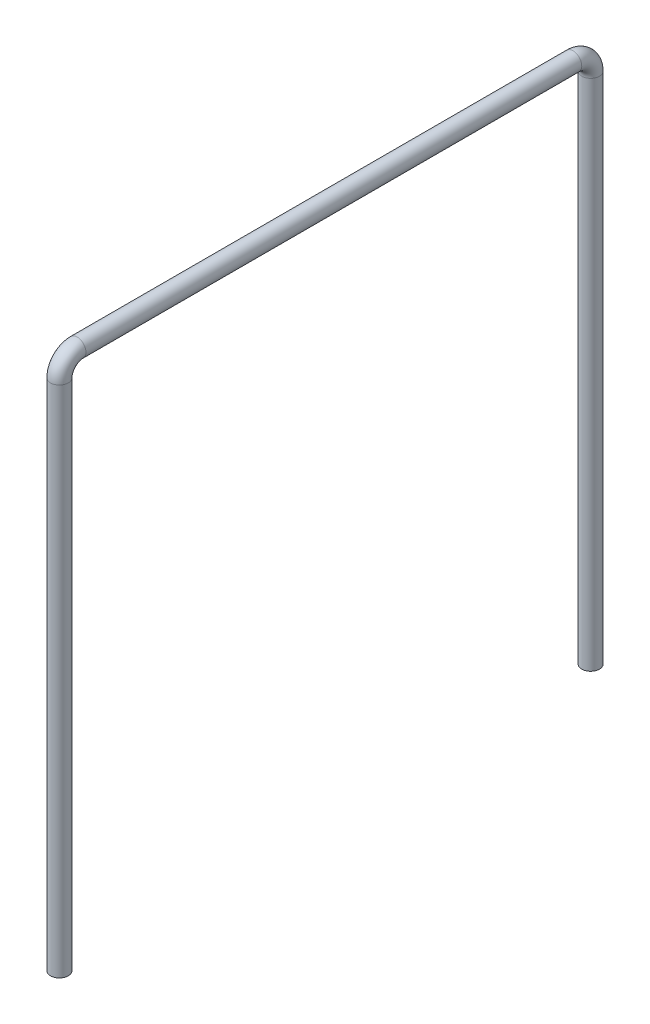
SolidWorks part; units mm, degrees
ref_plane "Plan de face" through (0, 0, 0) normal (0, 0, 1) x (1, 0, 0)
ref_plane "Plan de dessus" through (0, 0, 0) normal (0, 1, 0) x (1, 0, 0)
ref_plane "Plan de droite" through (0, 0, 0) normal (1, 0, 0) x (0, 0, -1)
sketch "Esquisse1" plane through (0, 0, 0) normal (0, 0, 1) x (1, 0, 0)
  line L1 (0, 0) -> (0, -5) construction
  circle A5 centre (0, 0) radius 5
  point P16 (0, 0)
sketch "Esquisse2" plane through (0, 0, 0) normal (1, 0, 0) x (0, 0, -1)
  line L0 (-150, -10) -> (-150, -300)
  line L2 (-140, 0) -> (140, 0)
  line L3 (0, 55) -> (0, -55) construction
  line L4 (150, -10) -> (150, -300)
  arc A0 (150, -10) -> (140, 0) centre (140, -10) ccw
  arc A1 (-150, -10) -> (-140, 0) centre (-140, -10) cw
  point P7 (0, 0)
  point P10 (150, 0)
  point P13 (-150, 0)
  dimension "D3" = 10
  dimension "D1" = 300
  dimension "D2" = 300
sweep "Balayage1" add profiles "Esquisse1" path "Esquisse2"
